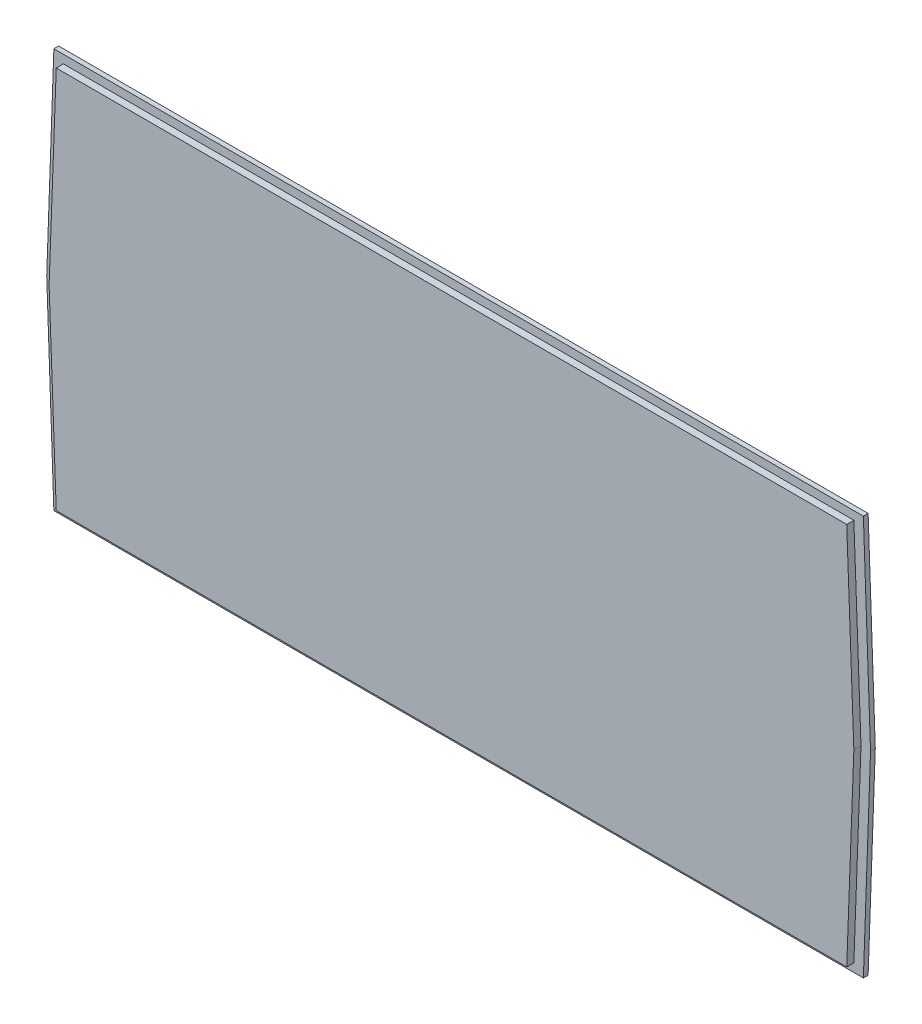
SolidWorks part; units mm, degrees
ref_plane "Front Plane" through (0, 0, 0) normal (0, 0, 1) x (1, 0, 0)
ref_plane "Top Plane" through (0, 0, 0) normal (0, 1, 0) x (1, 0, 0)
ref_plane "Right Plane" through (0, 0, 0) normal (1, 0, 0) x (0, 0, -1)
sketch "Sketch1" plane through (0, 0, 0) normal (0, 0, 1) x (1, 0, 0)
  line L1 (-85, 42) -> (85, 42)
  line L3 (-85, -42) -> (85, -42)
  line L5 (-85, 42) -> (85, -42) construction
  line L6 (-85, -42) -> (85, 42) construction
  line L7 (-86.5, 0) -> (-85, -42)
  line L8 (-85, 42) -> (-86.5, 0)
  line L9 (85, -42) -> (86.5, 0)
  line L10 (85, 42) -> (86.5, 0)
  point P0 (0, 0)
  dimension "D1" = 170
  dimension "D2" = 84
  dimension "D3" = 173
extrude "Boss-Extrude1" add sketch "Sketch1" along normal blind 1
sketch "Sketch2" plane through (0, 0, 1) normal (0, 0, 1) x (1, 0, 0)
  line L0 (-84.5, 0) -> (84.5, 0) construction
  line L1 (-83, 40.25) -> (83, 40.25)
  line L3 (-83, -40.25) -> (83, -40.25)
  line L5 (-83, 40.25) -> (83, -40.25) construction
  line L6 (-83, -40.25) -> (83, 40.25) construction
  line L7 (-83, -40.25) -> (-84.5, 0)
  line L8 (-84.5, 0) -> (-83, 40.25)
  line L9 (83, -40.25) -> (84.5, 0)
  line L10 (84.5, 0) -> (83, 40.25)
  point P0 (0, 0)
  dimension "D1" = 166
  dimension "D2" = 80.5
  dimension "D3" = 169
extrude "Boss-Extrude2" add sketch "Sketch2" along normal blind 1.5
